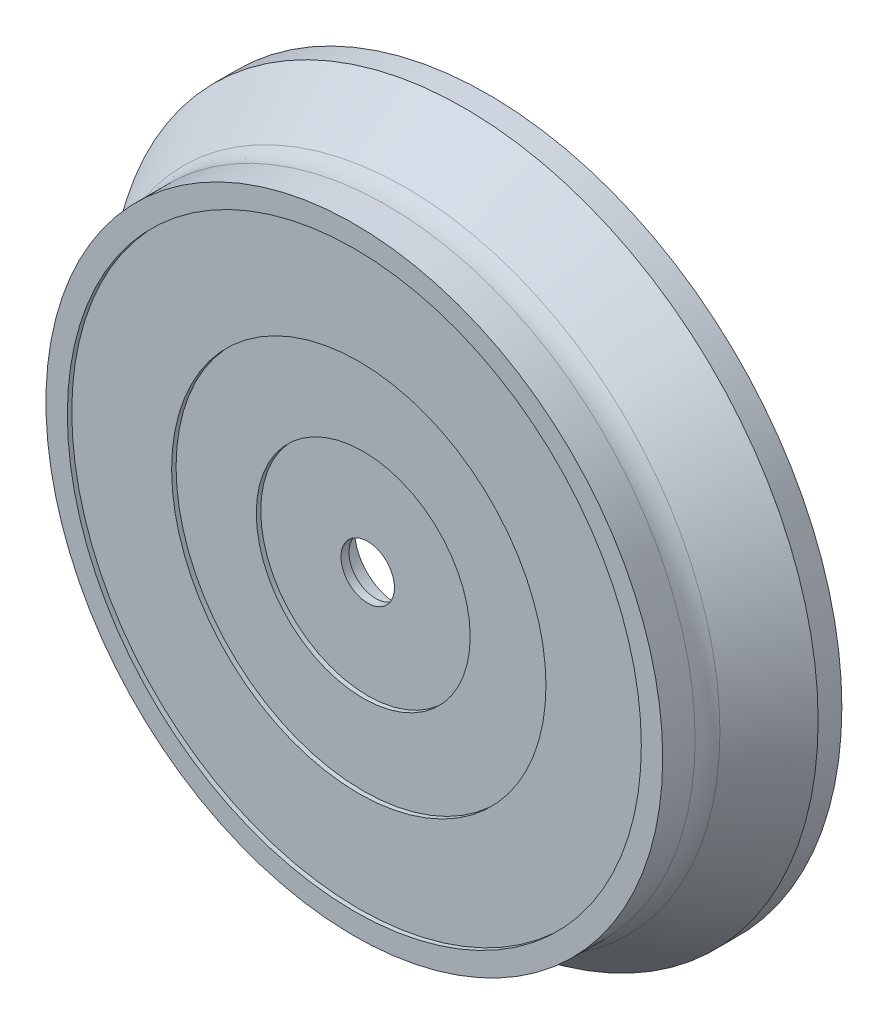
SolidWorks part; units mm, degrees
material "AISI 316 Annealed Stainless Steel Bar (SS)"
ref_plane "Front Plane" through (0, 0, 0) normal (1, 0, 0) x (0, 1, 0)
ref_plane "Top Plane" through (0, 0, 0) normal (0, 0, 1) x (0, 1, 0)
ref_plane "Right Plane" through (0, 0, 0) normal (0, 1, 0) x (-1, 0, 0)
ref_axis "Axis1" through (0, 0, 55) along (0, 0, -1)
sketch "Sketch1" plane through (0, 0, 0) normal (1, 0, 0) x (0, 1, 0)
  line L0 (-132.334, 0) -> (-107.334, 0)
  line L1 (-107.334, 0) -> (-107.334, -1.6667)
  line L2 (-107.334, -1.6667) -> (-70, -1.6667)
  line L3 (-70, -1.6667) -> (-70, -3.3333)
  line L4 (-70, -3.3333) -> (-40, -3.3333)
  line L5 (-40, -3.3333) -> (-40, -5)
  line L6 (-40, -5) -> (-10, -5)
  line L8 (-15.875, -16) -> (-107.334, -16)
  line L11 (-132.334, -50) -> (-132.334, 0)
  line L12 (0, 55) -> (0, -55) construction
  line L13 (-107.334, -16) -> (-130.334, -50)
  line L14 (-130.334, -50) -> (-132.334, -50)
  line L15 (-115.334, 0) -> (-115.334, -12.1079)
  line L16 (-117.5148, -19.2238) -> (-132.334, -41.1304)
  line L17 (-15.875, -8) -> (-15.875, -16)
  line L19 (-10, -5) -> (-10, -8)
  line L20 (-10, -8) -> (-15.875, -8)
  arc A1 (-115.334, -12.1079) -> (-117.5148, -19.2238) centre (-128.034, -12.1079) cw
  point P20 (-115.334, -16)
  dimension "D1" = 132.334
  dimension "D3" = 25
  dimension "D11" = 12.7
  dimension "D2" = 50
  dimension "D4" = 11
  dimension "D5" = 5
  dimension "D6" = 70
  dimension "D7" = 40
  dimension "D8" = 15.875
  dimension "D9" = 2
  dimension "D10" = 8
  dimension "D12" = 3
  dimension "D13" = 10
revolve "Revolve1" add sketch "Sketch1" angle 360 about axis through (0, 0, 55) along (0, 0, -1)
